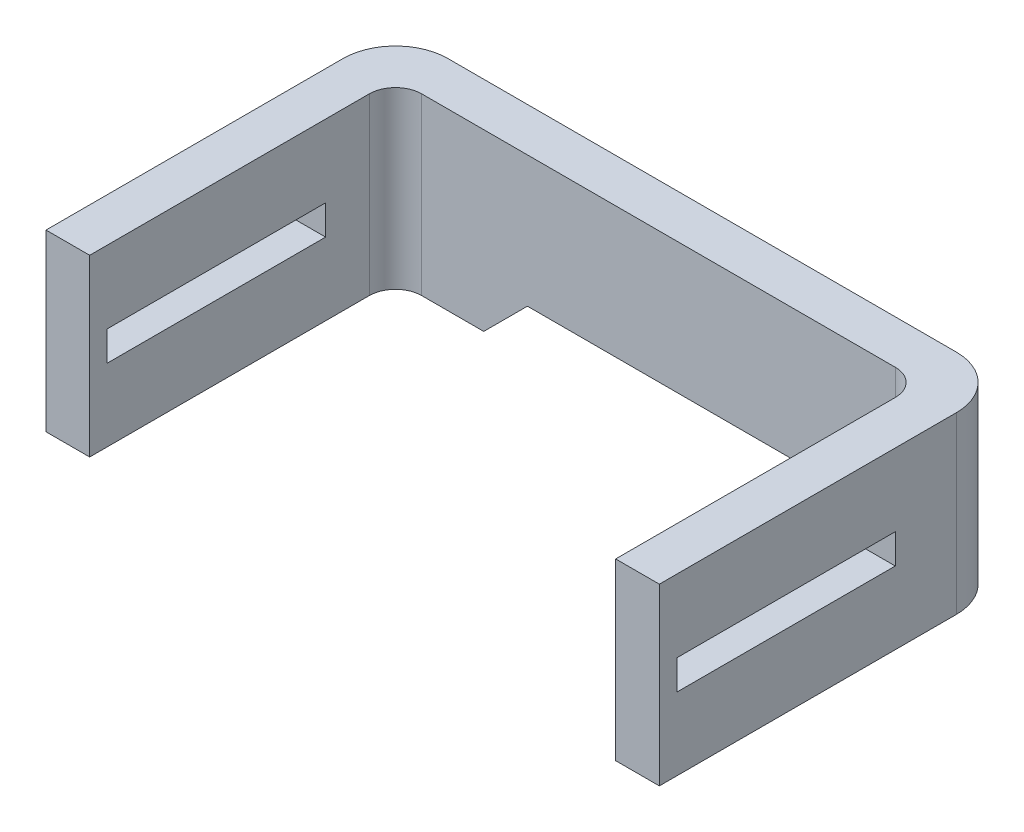
SolidWorks part; units mm, degrees
ref_plane "Ebene vorne" through (0, 0, 0) normal (0, 0, 1) x (1, 0, 0)
ref_plane "Ebene oben" through (0, 0, 0) normal (0, 1, 0) x (1, 0, 0)
ref_plane "Ebene rechts" through (0, 0, 0) normal (1, 0, 0) x (0, 0, -1)
sketch "Skizze1" plane through (0, 0, 0) normal (0, 1, 0) x (1, 0, 0)
  line L0 (0, 0) -> (0, 35)
  line L1 (0, 35) -> (60.2, 35)
  line L2 (60.2, 35) -> (60.2, 0)
  line L3 (60.2, 0) -> (65.2, 0)
  line L4 (65.2, 0) -> (65.2, 40)
  line L5 (65.2, 40) -> (-5, 40)
  line L6 (-5, 40) -> (-5, 0)
  line L7 (-5, 0) -> (0, 0)
  dimension "D1" = 60.2
  dimension "D2" = 5
  dimension "D3" = 35
  dimension "D4" = 40
extrude "Aufsatz-Linear austragen1" add sketch "Skizze1" along normal blind 20
sketch "Skizze2" plane through (-5, 0, 0) normal (-1, 0, 0) x (0, 0, 1)
  line L0 (-40, 10) -> (0, 10) construction
  line L1 (-40, 20) -> (-40, 0) construction
  line L2 (0, 20) -> (0, 0) construction
  line L4 (-27, 11.7) -> (-2, 11.7)
  line L5 (-27, 11.7) -> (-27, 8.3)
  line L6 (-27, 8.3) -> (-2, 8.3)
  line L7 (-2, 11.7) -> (-2, 8.3)
  line L8 (-27, 11.7) -> (-2, 8.3) construction
  line L9 (-27, 8.3) -> (-2, 11.7) construction
  point P10 (-14.5, 10)
  dimension "D1" = 2
  dimension "D2" = 3.4
  dimension "D3" = 25
extrude "Schnitt-Linear austragen1" cut sketch "Skizze2" against normal through all
fillet "Verrundung1" radius 3 2 edges at (60.2, 10, -35) (0, 10, -35)
fillet "Verrundung2" radius 6 2 edges at (65.2, 10, -40) (-5, 10, -40)
sketch "Skizze3" plane through (0, 0, -40) normal (0, 0, -1) x (-1, 0, 0)
  line L0 (-45.1, 5) -> (-15.1, 5)
  line L1 (-59.2, 0) -> (-1, 0) construction
  line L2 (-45.1, 5) -> (-50.1, 0)
  line L3 (-50.1, 0) -> (-10.1, 0)
  line L4 (-10.1, 0) -> (-15.1, 5)
  line L5 (-30.1, 20) -> (-30.1, 0) construction
  line L6 (-59.2, 20) -> (-1, 20) construction
  point P10 (-30.1, 5)
  dimension "D1" = 5
  dimension "D2" = 135
  dimension "D3" = 135
  dimension "D4" = 40
extrude "Schnitt-Linear austragen2" cut sketch "Skizze3" against normal through all
